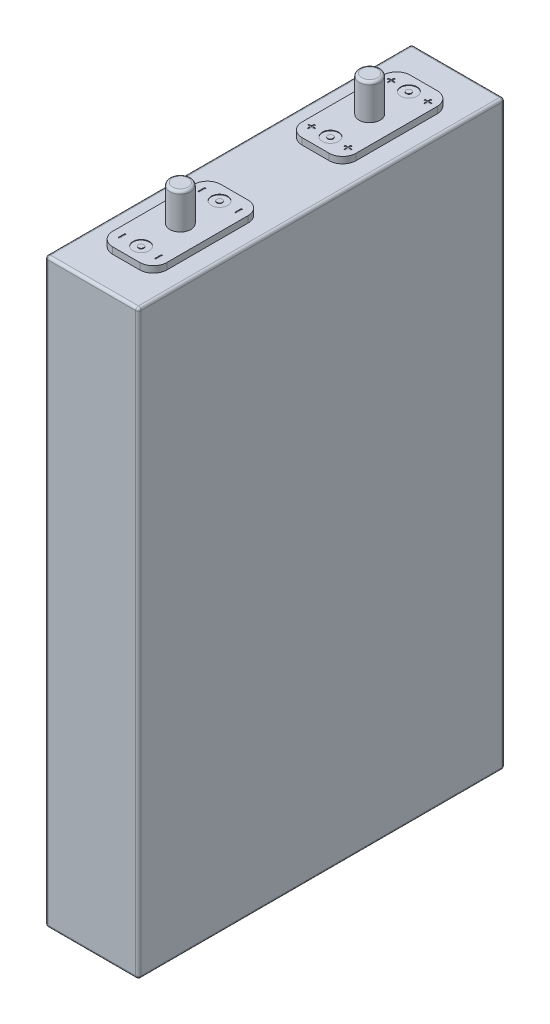
SolidWorks part; units mm, degrees
material "6063-T5"
ref_plane "Front" through (0, 0, 0) normal (0, 0, 1) x (1, 0, 0)
ref_plane "Top" through (0, 0, 0) normal (0, 1, 0) x (1, 0, 0)
ref_plane "Right" through (0, 0, 0) normal (1, 0, 0) x (0, 0, -1)
sketch "Sketch1" plane through (0, 0, 0) normal (1, 0, 0) x (0, 0, -1)
  line L1 (67.75, 107.5) -> (-67.75, 107.5)
  line L2 (67.75, 107.5) -> (67.75, -107.5)
  line L3 (67.75, -107.5) -> (-67.75, -107.5)
  line L4 (-67.75, 107.5) -> (-67.75, -107.5)
  line L5 (67.75, 107.5) -> (-67.75, -107.5) construction
  line L6 (67.75, -107.5) -> (-67.75, 107.5) construction
  point P0 (0, 0)
  dimension "D1" = 215
  dimension "D2" = 135.5
extrude "Boss-Extrude1" add sketch "Sketch1" along normal mid plane 34.5
sketch "Sketch2" plane through (0, 107.5, 0) normal (0, 1, 0) x (1, 0, 0)
  line L0 (0, 0) -> (47.4432, 0) construction
  circle A0 centre (0, -35) radius 3.9
  circle A1 centre (0, 35) radius 3.9
  dimension "D1" = 7.8
  dimension "D2" = 70
extrude "Boss-Extrude2" add sketch "Sketch2" along normal blind 15.5 separate body
sketch "Sketch3" plane through (0, 107.5, 0) normal (0, 1, 0) x (1, 0, 0)
  line L1 (-5, 55) -> (5, 55)
  line L2 (-10, 50) -> (-10, 20)
  line L3 (-5, 15) -> (5, 15)
  line L4 (10, 50) -> (10, 20)
  line L5 (-10, 55) -> (10, 15) construction
  line L6 (-10, 15) -> (10, 55) construction
  circle A1 centre (0, 35) radius 3.9 construction
  circle A2 centre (0, 35) radius 3.9
  arc A3 (5, 15) -> (10, 20) centre (5, 20) ccw
  arc A4 (-10, 20) -> (-5, 15) centre (-5, 20) ccw
  arc A5 (5, 55) -> (10, 50) centre (5, 50) cw
  arc A6 (-5, 55) -> (-10, 50) centre (-5, 50) ccw
  point P0 (0, 35)
  dimension "D3" = 5
  dimension "D1" = 20
  dimension "D2" = 40
extrude "Boss-Extrude3" add sketch "Sketch3" along normal blind 2.4 separate body
sketch "Sketch5" plane through (0, 109.9, 0) normal (0, 1, 0) x (1, 0, 0)
  line L0 (0, 35) -> (10, 35) construction
  line L1 (10, 20) -> (10, 50) construction
  circle A0 centre (0, 49.5) radius 3
  circle A1 centre (0, 20.5) radius 3
  circle A2 centre (0, 20.5) radius 1
  circle A3 centre (0, 49.5) radius 1
  dimension "D1" = 29
  dimension "D2" = 6
  dimension "D3" = 2
  dimension "D4" = 2
extrude "Cut-Extrude1" cut sketch "Sketch5" against normal blind 0.2
fillet "Fillet1" radius 1 4 edges at (17.25, 0, -67.75) (-17.25, 0, -67.75) (17.25, 0, 67.75) (-17.25, 0, 67.75)
fillet "Fillet2" radius 1 8 edges at (16.9571, 107.5, -67.4571) (0, 107.5, -67.75) (-16.9571, 107.5, -67.4571) (-17.25, 107.5, 0) (-16.9571, 107.5, 67.4571) (0, 107.5, 67.75) (16.9571, 107.5, 67.4571) (17.25, 107.5, 0)
fillet "Fillet3" radius 1 8 edges at (-16.9571, -107.5, 67.4571) (0, -107.5, 67.75) (16.9571, -107.5, 67.4571) (17.25, -107.5, 0) (16.9571, -107.5, -67.4571) (0, -107.5, -67.75) (-16.9571, -107.5, -67.4571) (-17.25, -107.5, 0)
mirror "Mirror1" about plane through (0, 0, 0) normal (0, 0, 1) of bodies 105
sketch "Sketch6" plane through (0, 109.9, 0) normal (0, 1, 0) x (1, 0, 0)
  line L0 (-7, 49.5) -> (-7, 48.5)
  line L1 (-7, 51) -> (-6.5, 51)
  line L2 (-7, 51) -> (-7, 50)
  line L3 (-7, 48.5) -> (-6.5, 48.5)
  line L4 (-6.5, 51) -> (-6.5, 50)
  line L5 (-8, 50) -> (-7, 50)
  line L6 (-8, 50) -> (-8, 49.5)
  line L7 (-8, 49.5) -> (-7, 49.5)
  line L8 (-5.5, 50) -> (-5.5, 49.5)
  line L9 (-6.5, 50) -> (-5.5, 50)
  line L10 (-6.5, 49.5) -> (-6.5, 48.5)
  line L11 (-6.5, 49.5) -> (-5.5, 49.5)
  line L12 (-10, 50) -> (-10, 20) construction
  line L13 (5, 55) -> (-5, 55) construction
  dimension "D1" = 0.5
  dimension "1" = 0.5
  dimension "D2" = 1
  dimension "D3" = 1
  dimension "D4" = 1
  dimension "D5" = 1
  dimension "D6" = 3
  dimension "D7" = 4
extrude "Cut-Extrude2" cut sketch "Sketch6" against normal blind 0.2
ref_plane "Plane1" through (0, 0, 0) normal (1, 0, 0) x (0, 0, -1)
mirror "Mirror2" about plane through (0, 0, 0) normal (1, 0, 0) of "Cut-Extrude2"
ref_plane "Plane2" through (0, 0, -35) normal (0, 0, 1) x (1, 0, 0)
mirror "Mirror3" about plane through (0, 0, -35) normal (0, 0, 1) of "Mirror2", "Cut-Extrude2"
sketch "Sketch7" plane through (0, 109.9, 0) normal (0, 1, 0) x (1, 0, 0)
  line L0 (-10, -50) -> (-10, -20) construction
  line L1 (-7, -48.5) -> (-6.5, -48.5)
  line L2 (-7, -48.5) -> (-7, -51)
  line L3 (-7, -51) -> (-6.5, -51)
  line L4 (-6.5, -48.5) -> (-6.5, -51)
  dimension "D1" = 0.5
  dimension "D2" = 2.5
  dimension "D3" = 3
  dimension "D4" = 4
extrude "Cut-Extrude3" cut sketch "Sketch7" against normal blind 0.2
ref_plane "Plane3" through (0, 0, 0) normal (-1, 0, 0) x (0, 0, 1)
mirror "Mirror4" about plane through (0, 0, 0) normal (-1, 0, 0) of "Cut-Extrude3"
ref_plane "Plane4" through (0, 0, 35) normal (0, 0, 1) x (1, 0, 0)
mirror "Mirror5" about plane through (0, 0, 35) normal (0, 0, 1) of "Mirror4", "Cut-Extrude3"
fillet "Fillet4" radius 1 1 edges at (0, 123, -38.9)
fillet "Fillet5" radius 1 1 edges at (0, 123, 38.9)
